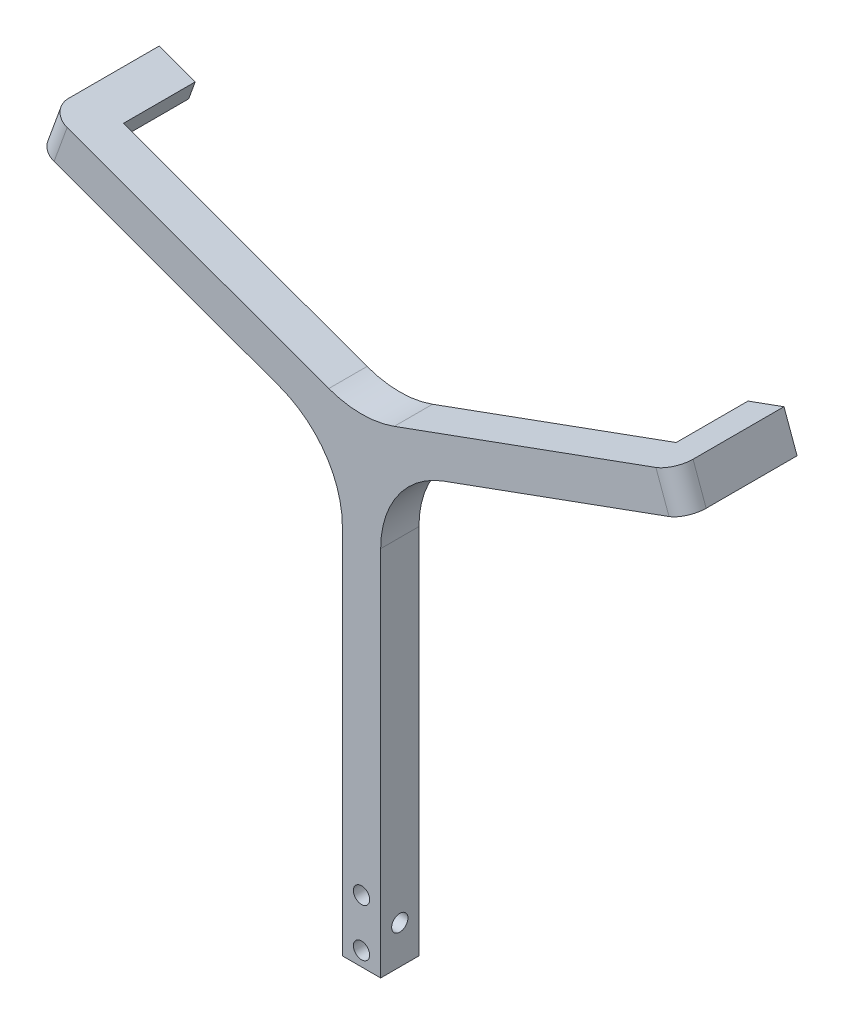
SolidWorks part; units mm, degrees
material "PLA"
ref_plane "Plan de face" through (0, 0, 0) normal (0, 0, 1) x (1, 0, 0)
ref_plane "Plan de dessus" through (0, 0, 0) normal (0, 1, 0) x (1, 0, 0)
ref_plane "Plan de droite" through (0, 0, 0) normal (1, 0, 0) x (0, 0, -1)
sketch "Esquisse1" plane through (0, 0, 0) normal (0, 0, 1) x (1, 0, 0)
  line L1 (0, 0) -> (136, 0) construction
  line L2 (0, 0) -> (0, 155) construction
  line L3 (0, 155) -> (136, 155) construction
  line L4 (136, 0) -> (136, 155) construction
  line L16 (64, 0) -> (64, 124.1884)
  line L17 (64, 124.1884) -> (0, 147.4825)
  line L18 (0, 147.4825) -> (2.7362, 155)
  line L19 (2.7362, 155) -> (68, 131.2459)
  line L20 (68, 131.2459) -> (133.2638, 155)
  line L21 (133.2638, 155) -> (136, 147.4825)
  line L22 (136, 147.4825) -> (72, 124.1884)
  line L23 (72, 124.1884) -> (72, 0)
  line L24 (72, 0) -> (64, 0)
  point P19 (68, 0)
  dimension "D1" = 136
  dimension "D2" = 155
  dimension "D3" = 8
  dimension "D4" = 68
  dimension "D5" = 110
  dimension "D6" = 110
  dimension "D7" = 140
  dimension "D8" = 8
  dimension "D9" = 8
  dimension "D10" = 68
extrude "Boss.-Extru.1" add sketch "Esquisse1" along normal blind 8
sketch "Esquisse2" plane through (0, 0, 0) normal (0, 0, -1) x (-1, 0, 0)
  line L0 (-72, 124.1884) -> (-136, 147.4825) construction
  line L1 (-136, 147.4825) -> (-133.2638, 155) construction
  line L2 (-133.2638, 155) -> (-68, 131.2459) construction
  line L3 (-132.2412, 146.1144) -> (-136, 147.4825)
  line L4 (-136, 147.4825) -> (-133.2638, 155)
  line L5 (-133.2638, 155) -> (-125.7463, 152.2638)
  line L6 (-127.1144, 148.5051) -> (-125.7463, 152.2638)
  line L7 (0, 147.4825) -> (-64, 124.1884) construction
  line L8 (-68, 131.2459) -> (-2.7362, 155) construction
  line L9 (-2.7362, 155) -> (0, 147.4825) construction
  line L10 (0, 147.4825) -> (-3.7588, 146.1144)
  line L11 (-10.2537, 152.2638) -> (-2.7362, 155)
  line L12 (-2.7362, 155) -> (0, 147.4825)
  line L13 (-10.2537, 152.2638) -> (-8.8856, 148.5051)
  line L14 (-132.2412, 146.1144) -> (-127.1144, 148.5051)
  line L15 (-8.8856, 148.5051) -> (-3.7588, 146.1144)
  dimension "D2" = 8
  dimension "D1" = 8
  dimension "D3" = 4
  dimension "D4" = 4
  dimension "D5" = 4
  dimension "D6" = 4
extrude "Boss.-Extru.2" add sketch "Esquisse2" along normal blind 15
fillet "Congé1" radius 20 3 edges at (72, 124.1884, 4) (64, 124.1884, 4) (68, 131.2459, 4)
fillet "Congé2" radius 4 2 edges at (134.6319, 151.2412, 8) (1.3681, 151.2412, 8)
sketch "Esquisse3" plane through (64, 0, 0) normal (-1, 0, 0) x (0, 0, 1)
  line L0 (4, 0) -> (4, 33.6289) construction
  line L1 (8, 0) -> (0, 0) construction
  circle A0 centre (4, 0) radius 7.5
  dimension "D1" = 15
extrude "Boss.-Extru.3" add sketch "Esquisse3" against normal up to surface (8 mm away) up to face at (72, 55.0921, 4)
sketch "Esquisse4" plane through (64, 0, 0) normal (-1, 0, 0) x (0, 0, 1)
  line L7 (4, 0) -> (4, 7.4852) construction
  line L11 (2.2536, 2.8) -> (5.7464, 2.8)
  line L12 (0.3981, -3.3) -> (8.2082, -3.3) construction
  arc A1 (2.2536, 2.8) -> (5.7464, 2.8) centre (4, 0) ccw
  point P10 (4, 6)
  point P11 (4, 6)
  dimension "D1" = 6.6
  dimension "D2" = 6.1
extrude "Enlèv. mat.-Extru.1" cut sketch "Esquisse4" against normal through all
sketch "Esquisse5" plane through (0, 0, 0) normal (0, 1, 0) x (1, 0, 0)
  line L1 (64, 3.5) -> (72, 3.5)
  line L2 (64, 3.5) -> (64, -11.5)
  line L3 (64, -11.5) -> (72, -11.5)
  line L4 (72, 3.5) -> (72, -11.5)
extrude "Enlèv. mat.-Extru.2" cut sketch "Esquisse5" against normal blind 7.5
sketch "Esquisse6" plane through (0, 0, 0) normal (0, -1, 0) x (1, 0, 0)
  line L1 (64, 11.5) -> (72, 11.5)
  line L2 (64, 11.5) -> (64, -3.5)
  line L3 (64, -3.5) -> (72, -3.5)
  line L4 (72, 11.5) -> (72, -3.5)
extrude "Enlèv. mat.-Extru.3" cut sketch "Esquisse6" against normal blind 32.5
sketch "Esquisse7" plane through (64, 0, 0) normal (-1, 0, 0) x (0, 0, 1)
  line L1 (8, 110.1842) -> (8, 32.5) construction
  line L2 (8, 32.5) -> (0, 32.5) construction
  circle A0 centre (4, 40.5) radius 1.5
  dimension "D3" = 3
  dimension "D1" = 8
  dimension "D2" = 4
extrude "Enlèv. mat.-Extru.4" cut sketch "Esquisse7" against normal up to surface (8 mm away) up to face at (72, 71.3421, 4)
hole_wizard "Dégagement M31" positions "Esquisse8" profile "Esquisse9" hole size "M3" standard "ISO"
sketch "Esquisse8" plane through (64, 0, 0) normal (-1, 0, 0) x (0, 0, 1)
  point P0 (4, 40.5)
sketch "Esquisse9" plane through (64, 40.5, 4) normal (0, 1, 0) x (0, 0, 1)
  line L0 (0, 0) -> (0, 11.0215)
  line L1 (0, 11.0215) -> (1.7, 10)
  line L2 (1.7, 10) -> (1.7, 0)
  line L5 (1.7, 0) -> (0, 0)
  line L10 (0, 11.0215) -> (-1.7, 10) construction
  line L11 (0, -6.35) -> (0, 107.95) construction
  dimension "Diamètre du perçage" = 3.4
  dimension "Profondeur du perçage" = 10
  dimension "Angle de pointe" = 118
sketch "Esquisse10" plane through (0, 0, 8) normal (0, 0, 1) x (1, 0, 0)
  line L0 (72, 32.5) -> (72, 110.1842) construction
  line L1 (72, 32.5) -> (64, 32.5) construction
  circle A0 centre (68, 35.5) radius 1.5
  circle A1 centre (68, 45.5) radius 1.5
  dimension "D3" = 3
  dimension "D4" = 3
  dimension "D1" = 3
  dimension "D2" = 13
  dimension "D5" = 4
  dimension "D6" = 4
extrude "Enlèv. mat.-Extru.5" cut sketch "Esquisse10" against normal up to surface (8 mm away) up to face at (68, 121.9647, 0)
hole_wizard "Dégagement M32" positions "Esquisse11" profile "Esquisse12" hole size "M3" standard "ISO"
sketch "Esquisse11" plane through (0, 0, 0) normal (0, 0, -1) x (-1, 0, 0)
  point P0 (-68, 45.5)
  point P3 (-68, 35.5)
sketch "Esquisse12" plane through (68, 45.5, 0) normal (1, 0, 0) x (0, 1, 0)
  line L0 (0, 0) -> (0, 11.0215)
  line L1 (0, 11.0215) -> (1.7, 10)
  line L2 (1.7, 10) -> (1.7, 0)
  line L5 (1.7, 0) -> (0, 0)
  line L10 (0, 11.0215) -> (-1.7, 10) construction
  line L11 (0, -6.35) -> (0, 107.95) construction
  dimension "Diamètre du perçage" = 3.4
  dimension "Profondeur du perçage" = 10
  dimension "Angle de pointe" = 118
equation "\"long_tot\"=155"
equation "\"espac_sub_arms\"= 120"
equation "\"épaiss_cadre\"=8"
equation "\"long_protub\"= 15"
equation "\"rayon_conge\"= 3"
equation "\"diam_axe\"= 5"
equation "\"D1@Esquisse1\"=\"espac_sub_arms\"+\"épaiss_cadre\"*2"
equation "\"D2@Esquisse1\"=\"long_tot\""
equation "\"D3@Esquisse1\"=\"épaiss_cadre\""
equation "\"D4@Esquisse1\"=\"D1@Esquisse1\"/2"
equation "\"D6@Esquisse1\"=\"D5@Esquisse1\""
equation "\"D8@Esquisse1\"=\"épaiss_cadre\""
equation "\"D9@Esquisse1\"=\"épaiss_cadre\""
equation "\"D10@Esquisse1\"=\"D4@Esquisse1\""
equation "\"D1@Boss.-Extru.1\"=\"épaiss_cadre\""
equation "\"D2@Esquisse2\"=\"épaiss_cadre\""
equation "\"D1@Boss.-Extru.2\"=\"long_protub\""
equation "\"D1@Esquisse2\"=\"épaiss_cadre\""
equation "\"D3@Esquisse2\"=\"D1@Esquisse2\"/2"
equation "\"D4@Esquisse2\"=\"D1@Esquisse2\"/2"
equation "\"D5@Esquisse2\"=\"D2@Esquisse2\"/2"
equation "\"D6@Esquisse2\"=\"D2@Esquisse2\"/2"
